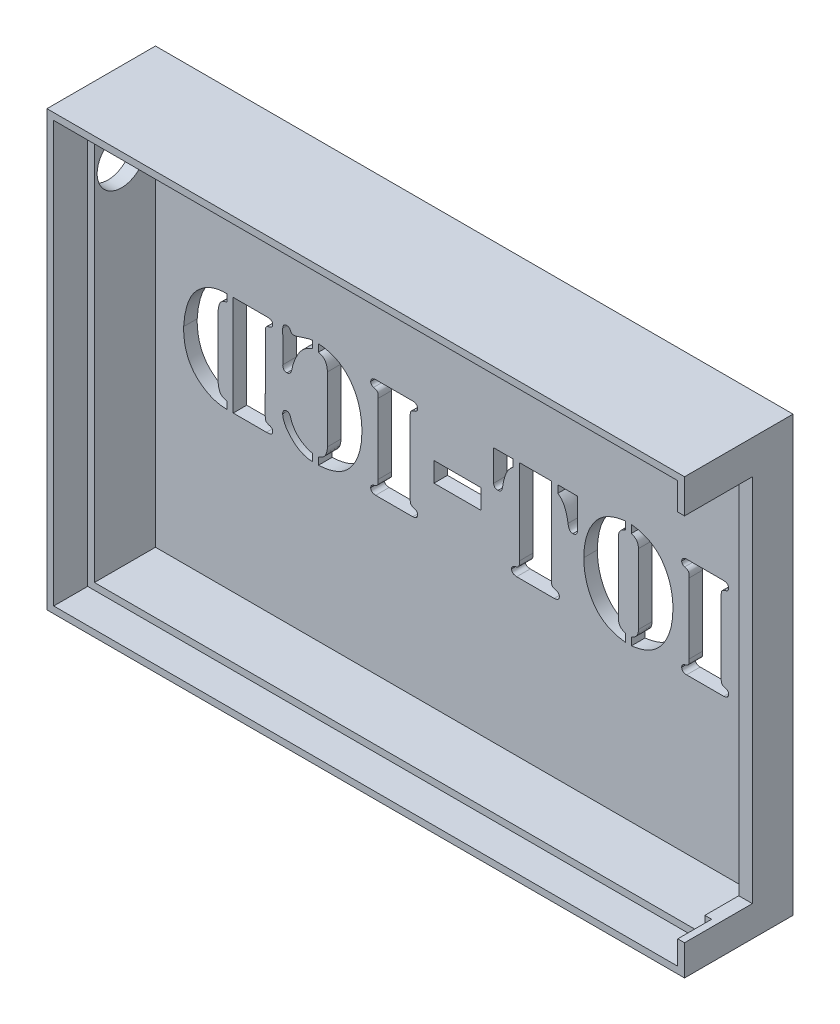
SolidWorks part; units mm, degrees
ref_plane "Front Plane" through (0, 0, 0) normal (0, 0, 1) x (1, 0, 0)
ref_plane "Top Plane" through (0, 0, 0) normal (0, 1, 0) x (1, 0, 0)
ref_plane "Right Plane" through (0, 0, 0) normal (1, 0, 0) x (0, 0, -1)
sketch "Sketch1" plane through (0, 0, 0) normal (0, 0, 1) x (1, 0, 0)
  line L0 (0, 46.1675) -> (0, -47.2288) construction
  line L1 (-66.8632, 0) -> (61.7689, 0) construction
  line L3 (-47, 32) -> (47, 32)
  line L4 (-47, 32) -> (-47, -32)
  line L5 (-47, -32) -> (47, -32)
  line L6 (47, 32) -> (47, -32)
  dimension "D1" = 94
  dimension "D2" = 47
  dimension "D3" = 64
  dimension "D4" = 32
extrude "Boss-Extrude1" add sketch "Sketch1" along normal blind 16
sketch "Sketch2" plane through (0, 0, 16) normal (0, 0, 1) x (1, 0, 0)
  line L0 (47, 32) -> (-47, 32) construction
  line L1 (-45, 30) -> (45, 30)
  line L2 (-45, 30) -> (-45, -30)
  line L3 (-45, -30) -> (45, -30)
  line L4 (45, 30) -> (45, -30)
  line L5 (-47, -32) -> (47, -32) construction
  line L6 (-47, 32) -> (-47, -32) construction
  line L7 (47, -32) -> (47, 32) construction
  dimension "D1" = 2
  dimension "D2" = 2
  dimension "D3" = 2
  dimension "D4" = 2
extrude "Cut-Extrude1" cut sketch "Sketch2" against normal blind 14
sketch "Sketch4" plane through (0, 0, 16) normal (0, 0, 1) x (1, 0, 0)
  line L0 (45, 30) -> (-45, 30) construction
  line L1 (-45, 30) -> (-45, -30) construction
  line L2 (-45, -30) -> (45, -30) construction
  line L3 (45, -30) -> (45, 30) construction
  line L5 (-46, 31) -> (46, 31)
  line L6 (-46, 31) -> (-46, -31)
  line L7 (-46, -31) -> (46, -31)
  line L8 (46, 31) -> (46, -31)
  dimension "D1" = 1
  dimension "D2" = 1
  dimension "D3" = 1
  dimension "D4" = 1
extrude "Cut-Extrude2" cut sketch "Sketch4" against normal blind 5
sketch "Sketch8" plane through (45, 0, 0) normal (-1, 0, 0) x (0, 0, 1)
  line L0 (16, 31) -> (16, -31) construction
  line L1 (16, 27) -> (6, 27)
  line L2 (16, 27) -> (16, -27.5)
  line L3 (16, -27.5) -> (6, -27.5)
  line L4 (6, 27) -> (6, -27.5)
  line L7 (2, -30) -> (2, 30) construction
  line L8 (2, -30) -> (11, -30) construction
  line L9 (2, 30) -> (11, 30) construction
  dimension "D1" = 2.5
  dimension "D2" = 3
  dimension "D3" = 4
extrude "Cut-Extrude4" cut sketch "Sketch8" against normal up to next
sketch "Sketch5" plane through (-47, 0, 0) normal (-1, 0, 0) x (0, 0, 1)
  line L0 (16, 32) -> (0, 32) construction
  line L1 (16, 32) -> (16, -32) construction
  circle A0 centre (7, 22) radius 3.6
  dimension "D1" = 7.2
  dimension "D2" = 10
  dimension "D3" = 9
extrude "Cut-Extrude3" cut sketch "Sketch5" against normal up to next
sketch "Sketch9" plane through (0, 0, 0) normal (0, 0, -1) x (-1, 0, 0)
  line L0 (47, -32) -> (-47, -32) construction
  line L1 (-47, -32) -> (-47, 32) construction
  text T0 "IOT-ICD" font "Stencil Std" height in points 56
  dimension "D1" = 24.8512
  dimension "D2" = 6.5689
extrude "Cut-Extrude5" cut sketch "Sketch9" against normal up to next
